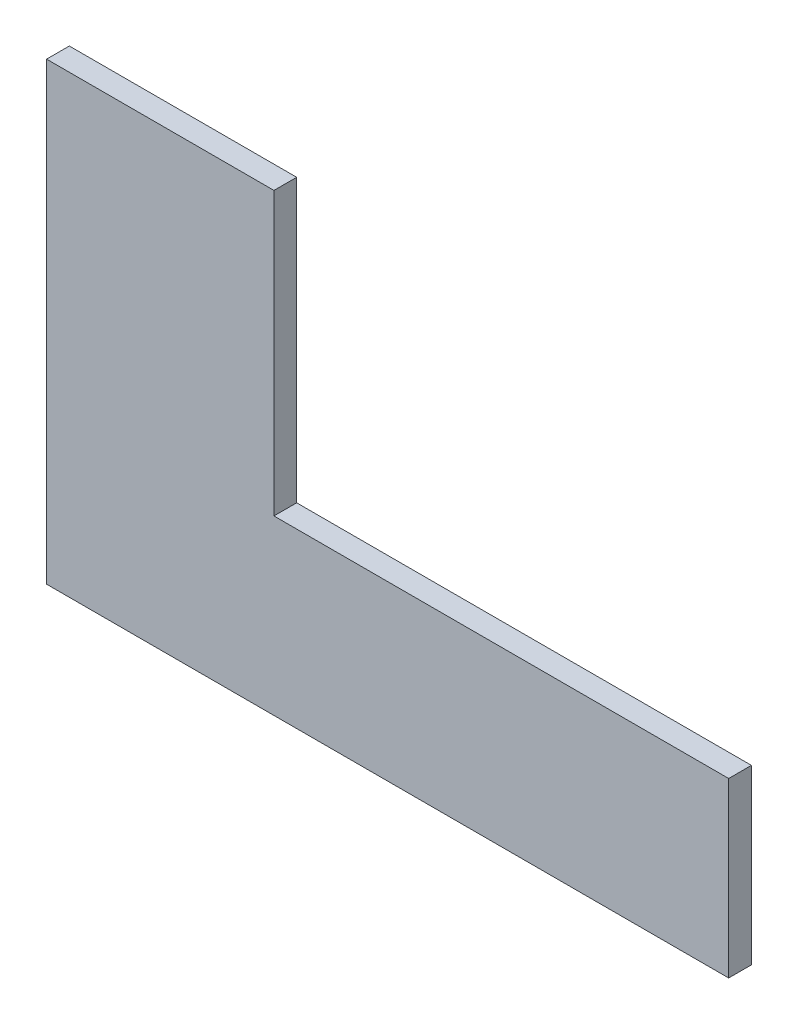
SolidWorks part; units mm, degrees
ref_plane "Front Plane" through (0, 0, 0) normal (0, 0, 1) x (1, 0, 0)
ref_plane "Top Plane" through (0, 0, 0) normal (0, 1, 0) x (1, 0, 0)
ref_plane "Right Plane" through (0, 0, 0) normal (1, 0, 0) x (0, 0, -1)
sketch "Sketch1" plane through (0, 0, 0) normal (0, 0, 1) x (1, 0, 0)
  line L0 (-86.8933, 50.459) -> (-36.8933, 50.459)
  line L1 (-36.8933, 50.459) -> (-36.8933, -11.541)
  line L2 (-36.8933, -11.541) -> (63.1067, -11.541)
  line L3 (63.1067, -11.541) -> (63.1067, -49.541)
  line L4 (63.1067, -49.541) -> (-86.8933, -49.541)
  line L5 (-86.8933, -49.541) -> (-86.8933, 50.459)
  point P3 (-72.837, -52.602)
  dimension "D1" = 38
  dimension "D2" = 100
  dimension "D3" = 50
  dimension "D4" = 100
extrude "Boss-Extrude1" add sketch "Sketch1" along normal blind 5
